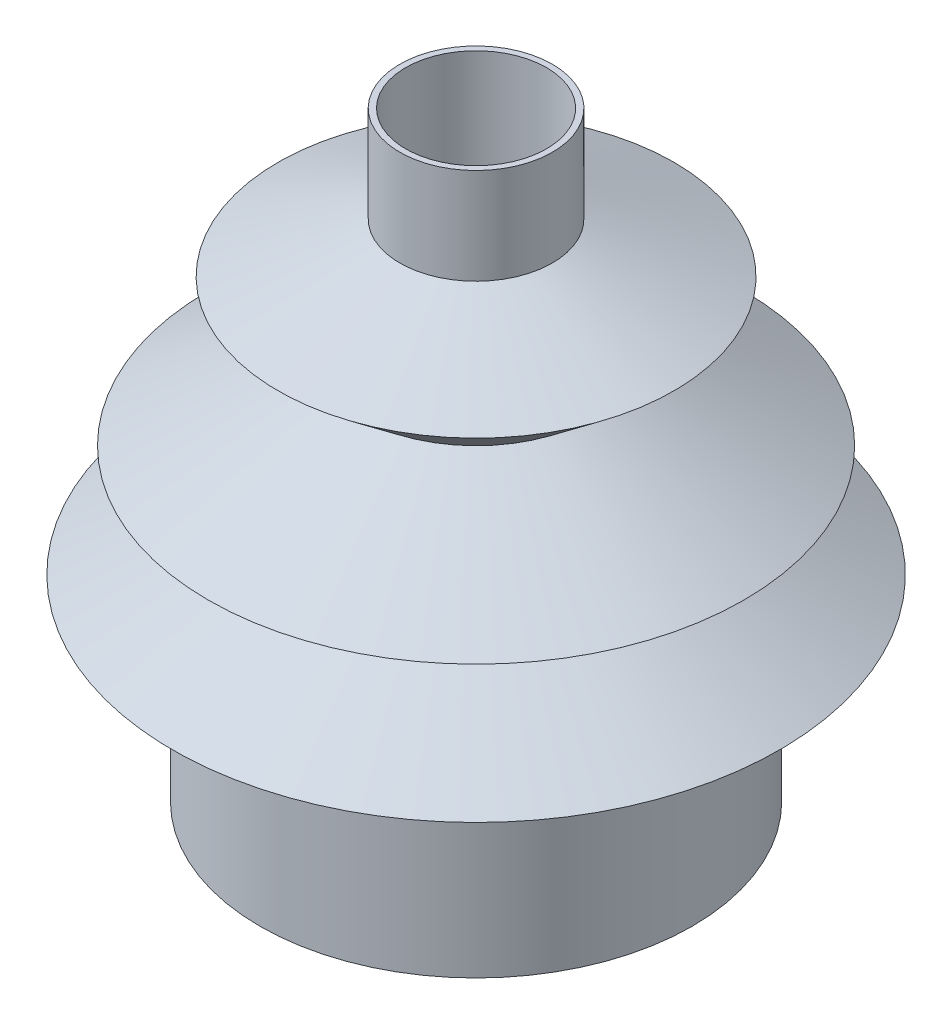
SolidWorks part; units mm, degrees
material "AISI 1020 Steel, Cold Rolled"
ref_plane "Front Plane" through (0, 0, 0) normal (0, 0, 1) x (1, 0, 0)
ref_plane "Top Plane" through (0, 0, 0) normal (0, 1, 0) x (1, 0, 0)
ref_plane "Right Plane" through (0, 0, 0) normal (1, 0, 0) x (0, 0, -1)
sketch "Sketch1" plane through (0, 0, 0) normal (0, 0, 1) x (1, 0, 0)
  line L0 (-9.2075, 5.9672) -> (-9.2075, -8.3485) construction
  line L1 (1.905, 16.5497) -> (1.905, -8.3485) construction
  line L14 (-9.2075, 6.939) -> (-9.2075, 5.9672)
  line L24 (-9.2075, 5.9672) -> (-9.2075, 0)
  line L25 (-9.2075, 0) -> (-6.9059, 0)
  line L26 (-9.2075, 6.939) -> (-12.9312, 8.37)
  line L27 (-12.9312, 8.37) -> (-7.2952, 11.5518)
  line L28 (-7.2952, 11.5518) -> (-11.4045, 13.1311)
  line L29 (-11.4045, 13.1311) -> (-5.0674, 16.7086)
  line L30 (-6.9059, 0) -> (-6.9059, 6.4162)
  line L31 (-6.9059, 7.3907) -> (-10.2853, 8.6894)
  line L32 (-10.2853, 8.6894) -> (-5.2599, 11.2009)
  line L33 (-5.2599, 11.2009) -> (-8.981, 12.6309)
  line L34 (-8.981, 12.6309) -> (-2.984, 16.1292)
  line L35 (0, 21.9795) -> (0, 6.4162) construction
  line L36 (-5.0674, 16.7086) -> (-8.4341, 19.3681)
  line L37 (-6.9059, 6.4162) -> (-6.9059, 7.3907)
  line L38 (-8.4341, 19.3681) -> (-3.25, 21.4913)
  line L39 (-2.984, 16.1292) -> (-2.984, 18.9162)
  line L40 (-2.984, 18.9162) -> (-4.437, 19.4746)
  line L41 (-4.437, 19.4746) -> (0, 21.9795)
  line L42 (0, 21.9795) -> (0, 25.578)
  line L43 (0, 25.578) -> (-3.25, 25.578)
  line L44 (-3.25, 25.578) -> (-3.25, 21.4913)
  line L45 (0, -7.0594) -> (0, 45.7771) construction
  line L46 (-19.0548, 0) -> (25.8409, 0) construction
  dimension "D1" = 1.905
  dimension "D2" = 11.1125
  dimension "D3" = 3.25
revolve "Revolve1" add sketch "Sketch1" angle 360 about L45
sketch "Sketch2" plane through (0, 25.578, 0) normal (0, 1, 0) x (1, 0, 0)
  circle A0 centre (0, 0) radius 3
  dimension "D1" = 6
extrude "Cut-Extrude1" cut sketch "Sketch2" against normal through all both and the other way through all
